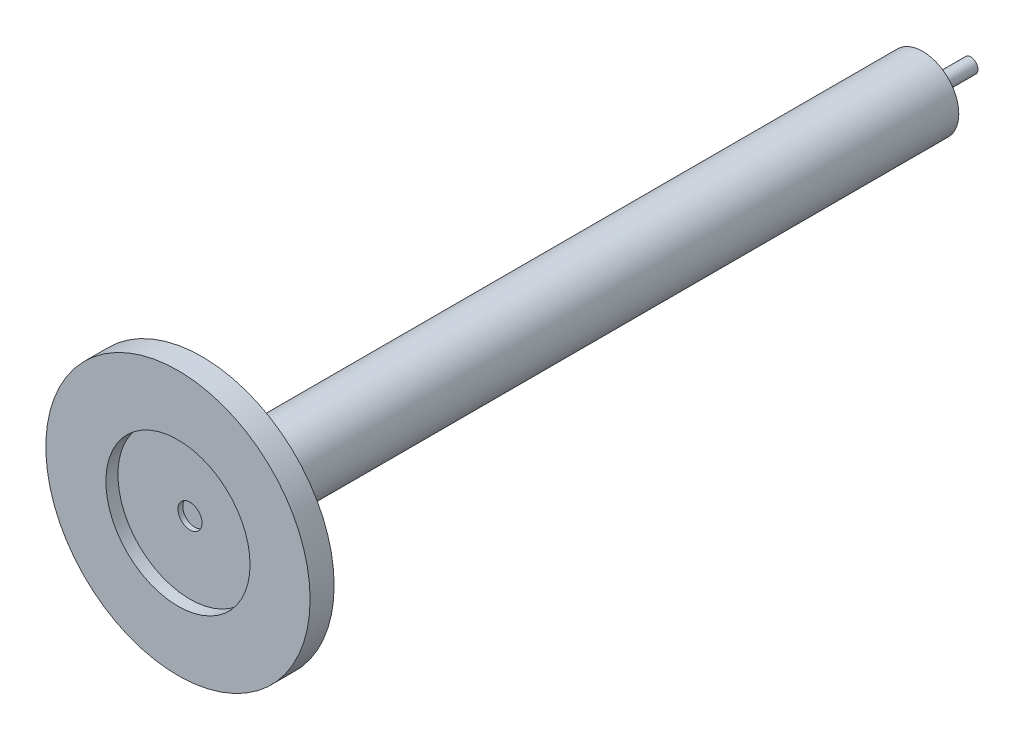
SolidWorks part; units mm, degrees
ref_plane "Front Plane" through (0, 0, 0) normal (0, 0, 1) x (1, 0, 0)
ref_plane "Top Plane" through (0, 0, 0) normal (0, 1, 0) x (1, 0, 0)
ref_plane "Right Plane" through (0, 0, 0) normal (1, 0, 0) x (0, 0, -1)
sketch "Sketch1" plane through (0, 0, 0) normal (0, 0, 1) x (1, 0, 0)
  circle A0 centre (0, 0) radius 139.7
  dimension "D1" = 279.4
extrude "Boss-Extrude1" add sketch "Sketch1" along normal blind 25.4
sketch "Sketch3" plane through (0, 0, 0) normal (0, 0, -1) x (-1, 0, 0)
  circle A0 centre (0, 0) radius 38.1
  dimension "D1" = 76.2
extrude "Boss-Extrude2" add sketch "Sketch3" along normal blind 762
sketch "Sketch5" plane through (0, 0, -762) normal (0, 0, -1) x (-1, 0, 0)
  circle A0 centre (0, 0) radius 7.62
  dimension "D1" = 15.24
extrude "Boss-Extrude3" add sketch "Sketch5" along normal blind 50.8
sketch "Sketch7" plane through (0, 0, 25.4) normal (0, 0, 1) x (1, 0, 0)
  circle A0 centre (0, 0) radius 76.2
  dimension "D1" = 152.4
extrude "Cut-Extrude1" cut sketch "Sketch7" against normal blind 12.7
sketch "Sketch9" plane through (0, 0, 12.7) normal (0, 0, 1) x (1, 0, 0)
  circle A0 centre (0, 0) radius 12.7
  dimension "D1" = 25.4
extrude "Cut-Extrude3" cut sketch "Sketch9" against normal blind 5.08 contours A0
